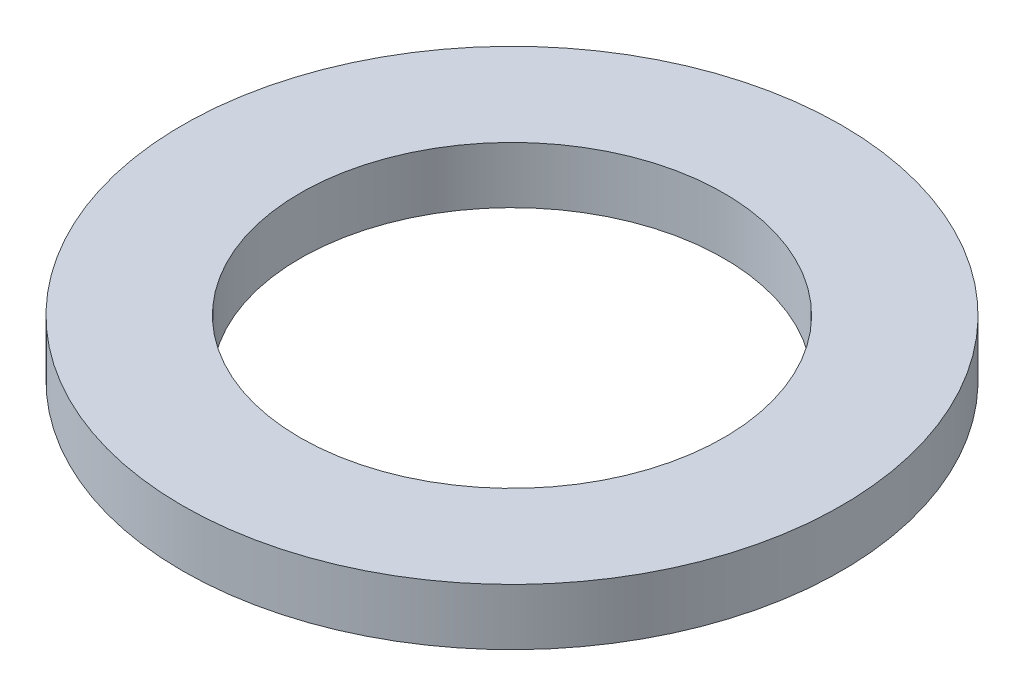
SolidWorks part; units mm, degrees
material "Kiefer"
ref_plane "Ebene vorne" through (0, 0, 0) normal (0, 0, 1) x (1, 0, 0)
ref_plane "Ebene oben" through (0, 0, 0) normal (0, 1, 0) x (1, 0, 0)
ref_plane "Ebene rechts" through (0, 0, 0) normal (1, 0, 0) x (0, 0, -1)
sketch "Skizze1" plane through (0, 0, 0) normal (0, 1, 0) x (1, 0, 0)
  circle A0 centre (0, 0) radius 17.5
  dimension "D1" = 35
extrude "Aufsatz-Linear austragen1" add sketch "Skizze1" along normal blind 3
sketch "Skizze2" plane through (0, 3, 0) normal (0, 1, 0) x (1, 0, 0)
  circle A0 centre (0, 0) radius 11.25
  dimension "D1" = 22.5
extrude "Schnitt-Linear austragen1" cut sketch "Skizze2" against normal through all
